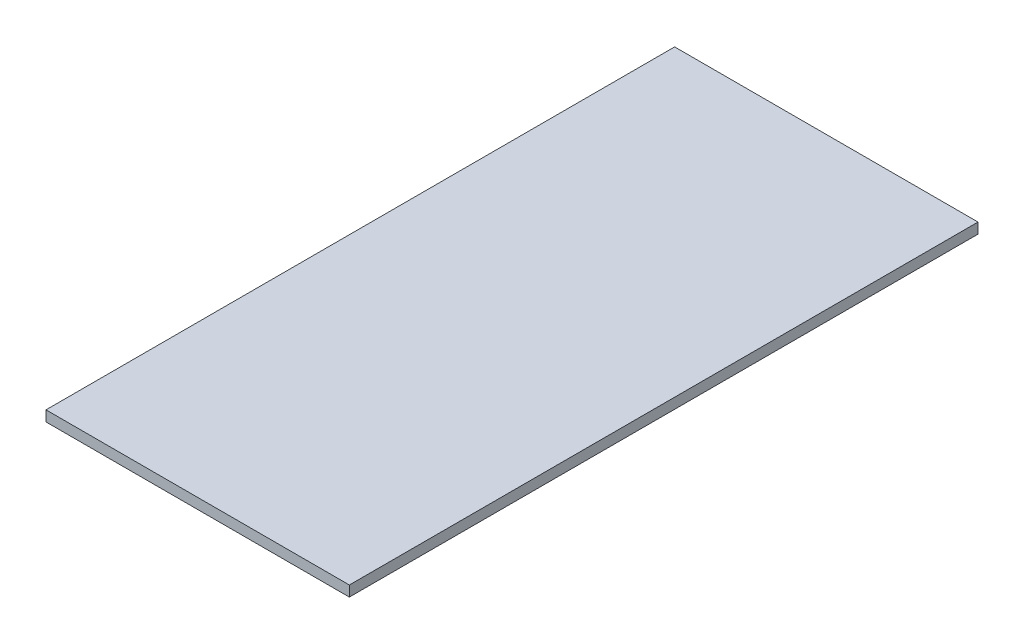
SolidWorks part; units mm, degrees
material "Solar Panel"
ref_plane "Front Plane" through (0, 0, 0) normal (0, 0, 1) x (1, 0, 0)
ref_plane "Top Plane" through (0, 0, 0) normal (0, 1, 0) x (1, 0, 0)
ref_plane "Right Plane" through (0, 0, 0) normal (1, 0, 0) x (0, 0, -1)
sketch "Sketch1" plane through (0, 0, 0) normal (0, 0, 1) x (1, 0, 0)
  line L1 (-288.7, 10) -> (288.7, 10)
  line L2 (-288.7, 10) -> (-288.7, -10)
  line L3 (-288.7, -10) -> (288.7, -10)
  line L4 (288.7, 10) -> (288.7, -10)
  line L5 (-288.7, 10) -> (288.7, -10) construction
  line L6 (-288.7, -10) -> (288.7, 10) construction
  point P0 (0, 0)
  dimension "D1" = 20
  dimension "D2" = 577.4
extrude "Boss-Extrude1" add sketch "Sketch1" along normal blind 1196.5
